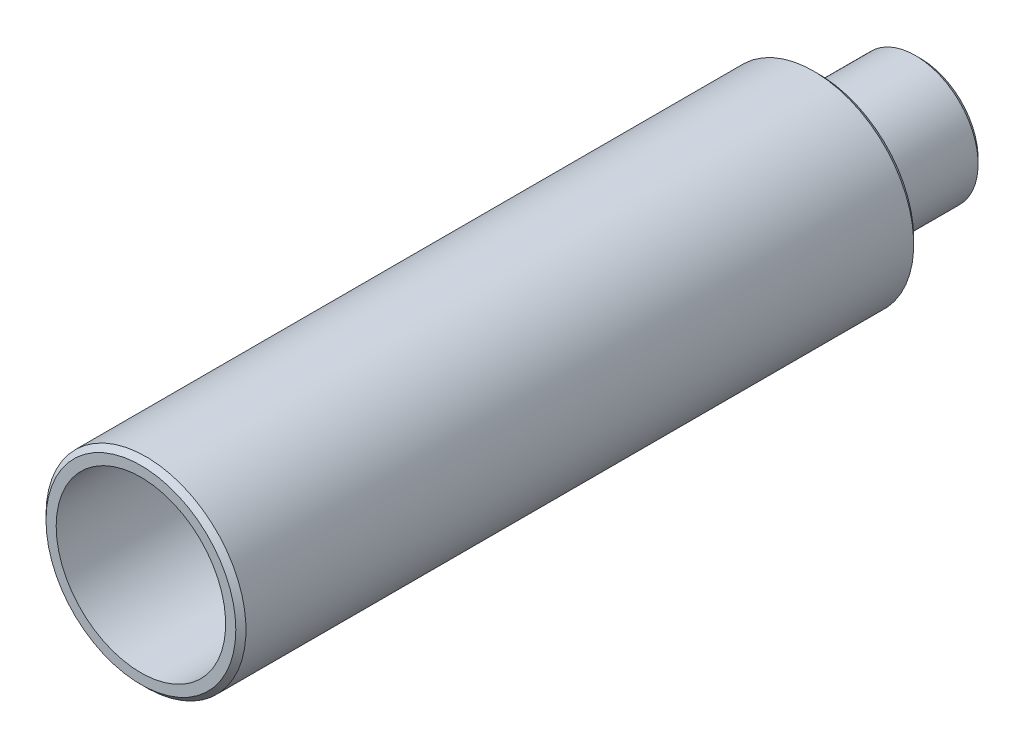
SolidWorks part; units mm, degrees
material "1060 Сплав"
ref_plane "Спереди" through (0, 0, 0) normal (0, 0, 1) x (1, 0, 0)
ref_plane "Сверху" through (0, 0, 0) normal (0, 1, 0) x (1, 0, 0)
ref_plane "Справа" through (0, 0, 0) normal (1, 0, 0) x (0, 0, -1)
sketch "Эскиз1" plane through (0, 0, 0) normal (0, 1, 0) x (1, 0, 0)
  line L0 (5, -40) -> (5, -2.5)
  line L1 (0, 0) -> (1.55, 0)
  line L2 (0, 0) -> (0, -40)
  line L3 (0, -40) -> (5.6, -40)
  line L4 (5.9, -0.3) -> (5.9, -39.7)
  line L5 (0, 0) -> (1.55, 0)
  line L6 (0, 0) -> (0, 6)
  line L7 (0, 6) -> (3.4, 6)
  line L8 (3.7, 0) -> (3.7, 5.7)
  line L9 (3, 6) -> (3, 2.5)
  line L10 (3.7, 0) -> (5.6, 0)
  line L11 (3, 2.5) -> (1.85, 2.5)
  line L12 (2.85, -2.5) -> (1.55, -1.2)
  line L13 (5, -2.5) -> (2.85, -2.5)
  line L14 (1.55, 2.2) -> (1.55, -1.2)
  line L15 (1.85, 2.5) -> (1.55, 2.2)
  line L16 (3.4, 6) -> (3.7, 5.7)
  line L17 (5.6, 0) -> (5.9, -0.3)
  line L18 (5.6, -40) -> (5.9, -39.7)
  point P1 (5.9, -40)
  point P3 (5.9, 0)
  point P5 (3.7, 6)
  point P13 (1.55, -2.5)
  point P15 (1.55, 2.5)
  dimension "D1" = 5
  dimension "D2" = 5.9
  dimension "D3" = 40
  dimension "D4" = 6
  dimension "D5" = 3.7
  dimension "D6" = 3
  dimension "D7" = 3.5
  dimension "D8" = 37.5
  dimension "D9" = 1.55
revolve "Повернуть1" add sketch "Эскиз1" angle 360 about L2
cosmetic thread "Условное изображение резьбы1" parameters "D1"=26, "D2"=11.3135
cosmetic thread "Условное изображение резьбы2" [suppressed] parameters "D1"=26, "D2"=11.3135
cosmetic thread "Условное изображение резьбы3" [suppressed] parameters "D1"=5, "D2"=6.4
sketch "Эскиз2" plane through (0, 0, 40) normal (0, 0, 1) x (1, 0, 0)
  circle A0 centre (0, 0) radius 6
  dimension "D1" = 12
curve "Спираль1" [suppressed] pitch 0.8 height 25.6 turns 32
